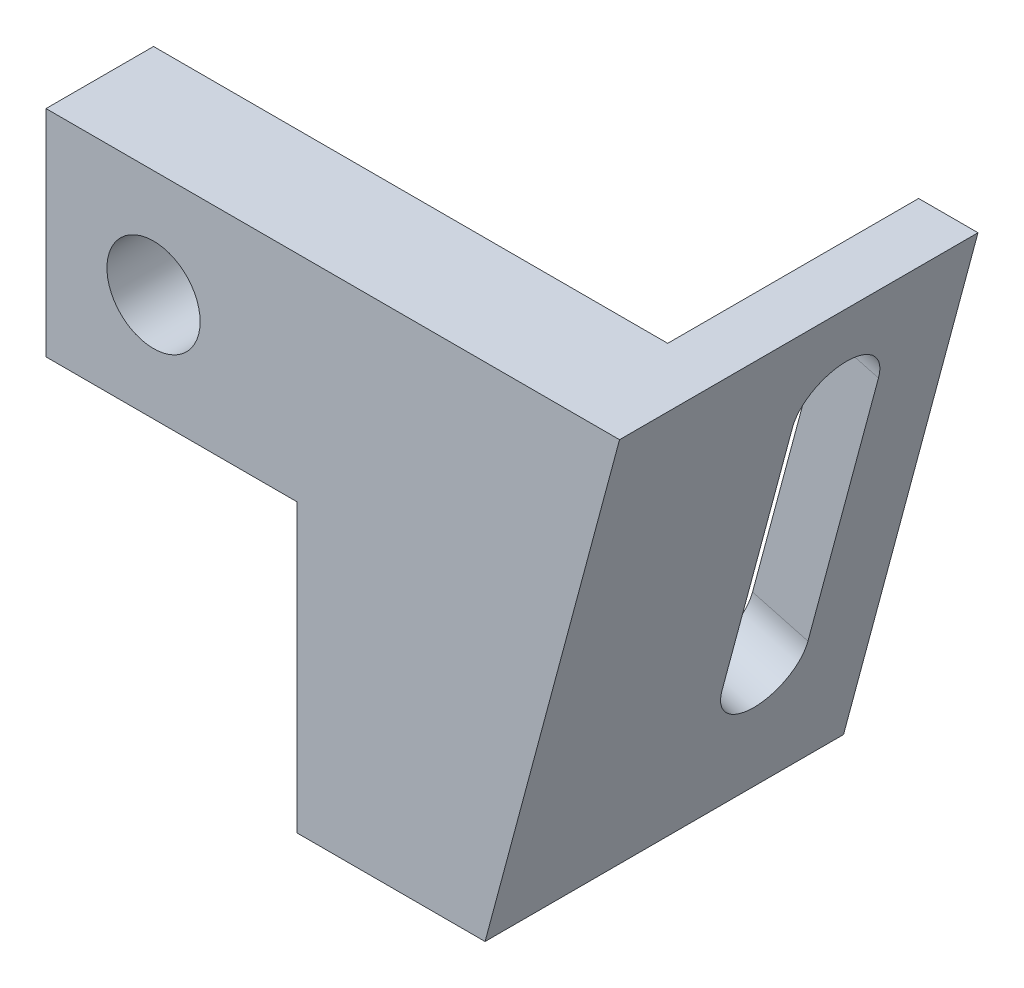
SolidWorks part; units mm, degrees
ref_plane "Plano frontal" through (0, 0, 0) normal (0, 0, 1) x (1, 0, 0)
ref_plane "Plano superior" through (0, 0, 0) normal (0, 1, 0) x (1, 0, 0)
ref_plane "Plano direito" through (0, 0, 0) normal (1, 0, 0) x (0, 0, -1)
sketch "Esboço1" plane through (0, 0, 0) normal (0, 0, 1) x (1, 0, 0)
  line L0 (-31.6168, 46.5709) -> (-50.3733, -23.4291)
  line L1 (-50.3733, -23.4291) -> (-76.6168, -23.4291)
  line L2 (-76.6168, -23.4291) -> (-76.6168, 16.5709)
  line L3 (-76.6168, 16.5709) -> (-111.6168, 16.5709)
  line L4 (-111.6168, 16.5709) -> (-111.6168, 46.5709)
  line L5 (-111.6168, 46.5709) -> (-31.6168, 46.5709)
  circle A0 centre (-96.6168, 31.5709) radius 6.5
  point P8 (0, 0)
  point P9 (0, 0)
  dimension "D1" = 15
  dimension "D3" = 13
  dimension "D2" = 15
  dimension "D4" = 80
  dimension "D5" = 75
  dimension "D6" = 35
  dimension "D7" = 30
  dimension "D8" = 70
extrude "Ressalto-extrusão1" add sketch "Esboço1" along normal blind 15
sketch "Esboço2" plane through (0, 0, 0) normal (0, 0, -1) x (-1, 0, 0)
  line L0 (58.6555, -23.4291) -> (39.8991, 46.5709)
  line L1 (76.6168, -23.4291) -> (50.3733, -23.4291) construction
  line L2 (31.6168, 46.5709) -> (111.6168, 46.5709) construction
  line L3 (50.3733, -23.4291) -> (31.6168, 46.5709) construction
  line L4 (39.8991, 46.5709) -> (31.6168, 46.5709)
  line L5 (31.6168, 46.5709) -> (50.3733, -23.4291)
  line L6 (50.3733, -23.4291) -> (58.6555, -23.4291)
  dimension "D1" = 8
extrude "Ressalto-extrusão2" add sketch "Esboço2" along normal blind 35
sketch "Esboço3" plane through (-41.1417, 11.0239, 0) normal (0.9659, -0.2588, 0) x (0, 0, -1)
  line L2 (-15, 36.801) -> (35, 36.801) construction
  line L3 (35, 36.801) -> (35, -35.6683) construction
  line L4 (13, 21.801) -> (13, -16.199)
  line L5 (25, 21.801) -> (25, -16.199)
  arc A0 (25, 21.801) -> (13, 21.801) centre (19, 21.801) ccw
  arc A1 (13, -16.199) -> (25, -16.199) centre (19, -16.199) ccw
  dimension "D1" = 12
  dimension "D2" = 38
  dimension "D3" = 15
  dimension "D4" = 16
extrude "Corte-extrusão1" cut sketch "Esboço3" against normal up to next
